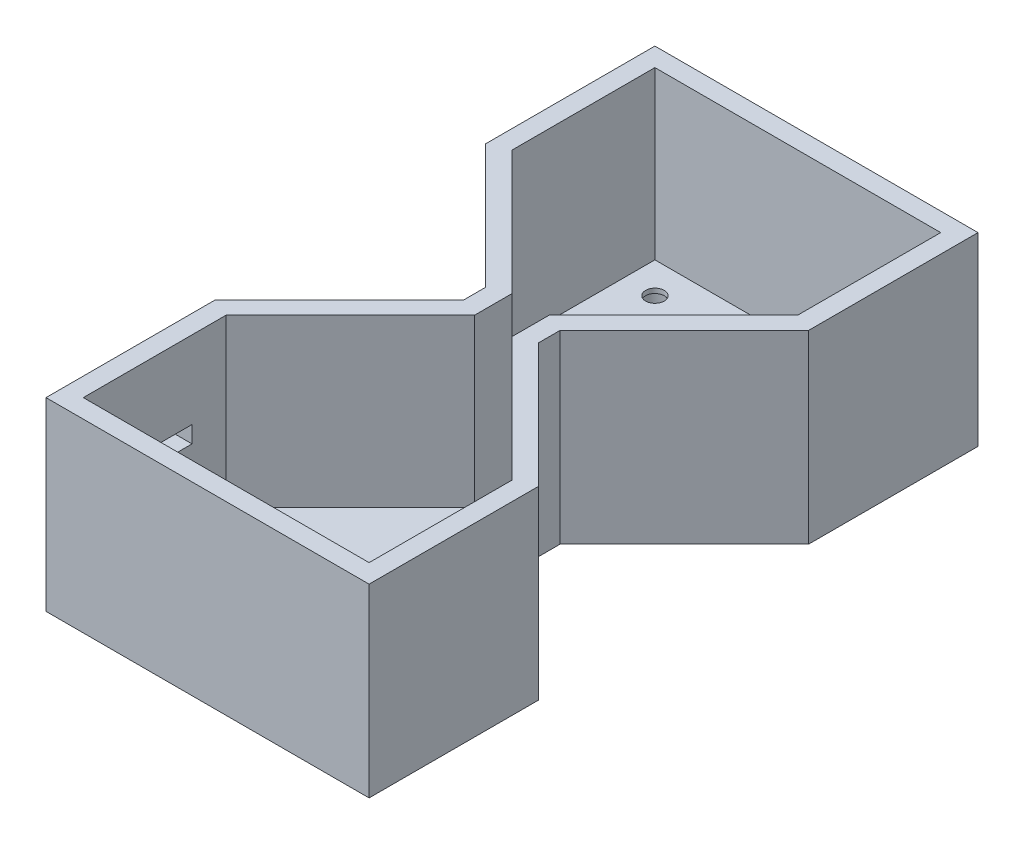
SolidWorks part; units mm, degrees
ref_plane "前视基准面" through (0, 0, 0) normal (0, 0, 1) x (1, 0, 0)
ref_plane "上视基准面" through (0, 0, 0) normal (0, 1, 0) x (1, 0, 0)
ref_plane "右视基准面" through (0, 0, 0) normal (1, 0, 0) x (0, 0, -1)
other "Configuration Table"
sketch "草图2" plane through (0, 0, 0) normal (0, 1, 0) x (1, 0, 0)
  line L0 (0, 0) -> (46, 0)
  line L1 (46, 0) -> (46, 23)
  line L2 (0, 0) -> (0, 23)
  line L3 (46, 23) -> (26.0002, 42.9998)
  line L4 (0, 23) -> (19.9998, 42.9998)
  line L5 (26.0002, 42.9998) -> (26.0002, 48.9998)
  line L6 (19.9998, 42.9998) -> (19.9998, 48.9998)
  line L7 (19.9998, 48.9998) -> (0, 68.9996)
  line L8 (26.0002, 48.9998) -> (46, 68.9996)
  line L9 (0, 68.9996) -> (0, 91.9996)
  line L10 (46, 68.9996) -> (46, 91.9996)
  line L11 (46, 91.9996) -> (0, 91.9996)
extrude "凸台-拉伸2" add sketch "草图2" along normal blind 26.8 contours L0 L1 L3 L5 L8 L10 L11 L9 L7 L6 L4 L2
shell "抽壳2" thickness 3
sketch "草图8" plane through (0, -3, 0) normal (0, -1, 0) x (1, 0, 0)
  circle A0 centre (5, -5) radius 1.7
  circle A1 centre (41, -5) radius 1.7
  circle A2 centre (5, -87) radius 1.7
  circle A3 centre (41, -87) radius 1.7
  point P8 (0, 0)
  point P9 (0, 0)
  point P10 (0, 0)
hole_wizard "Ø3.0mm 暗销孔1" positions "3D草图3" profile "草图14" hole size "Ø3.0" standard "ANSI Metric"
sketch3d "3D草图3"
  point P0 (5, -3, -5)
  point P3 (41, -3, -5)
  point P6 (41, -3, -87)
  point P9 (5, -3, -87)
sketch "草图14" plane through (5, -3, -5) normal (1, 0, 0) x (0, 0, -1)
  line L0 (0, 0) -> (0, 5.9013)
  line L1 (0, 5.9013) -> (1.5, 5)
  line L2 (1.5, 5) -> (1.5, 0)
  line L5 (1.5, 0) -> (0, 0)
  line L10 (0, 5.9013) -> (-1.5, 5) construction
  line L11 (0, -6.35) -> (0, 107.95) construction
  dimension "孔直径" = 3
  dimension "孔深度" = 5
  dimension "导头角度" = 118
hole_wizard "Ø3.0mm 暗销孔2" positions "3D草图4" profile "草图15" hole size "Ø3.0" standard "ANSI Metric"
sketch3d "3D草图4"
  point P0 (5, -3, -5)
  point P3 (41, -3, -5)
  point P6 (41, -3, -87)
  point P9 (5, -3, -87)
sketch "草图15" plane through (5, -3, -5) normal (1, 0, 0) x (0, 0, -1)
  line L0 (0, 0) -> (0, 3.1524)
  line L1 (0, 3.1524) -> (2.75, 1.5)
  line L2 (2.75, 1.5) -> (2.75, 0)
  line L5 (2.75, 0) -> (0, 0)
  line L10 (0, 3.1524) -> (-2.75, 1.5) construction
  line L11 (0, -6.35) -> (0, 107.95) construction
  dimension "孔直径" = 5.5
  dimension "孔深度" = 1.5
  dimension "导头角度" = 118
sketch "草图16" plane through (0, 0, 0) normal (1, 0, 0) x (0, 0, -1)
  line L0 (0, 0) -> (23, 0) construction
  line L5 (12.5, 0) -> (17.5, 0)
  line L6 (12.5, 0) -> (12.5, 11.6)
  line L7 (12.5, 11.6) -> (17.5, 11.6)
  line L8 (17.5, 0) -> (17.5, 11.6)
  line L10 (12.5, 11.6) -> (17.5, 11.6)
  line L11 (12.5, 11.6) -> (12.5, 14.3)
  line L12 (12.5, 14.3) -> (17.5, 14.3)
  line L13 (17.5, 11.6) -> (17.5, 14.3)
extrude "切除-拉伸3" cut sketch "草图16" against normal blind 10 contours L7 L13 L12 L11
